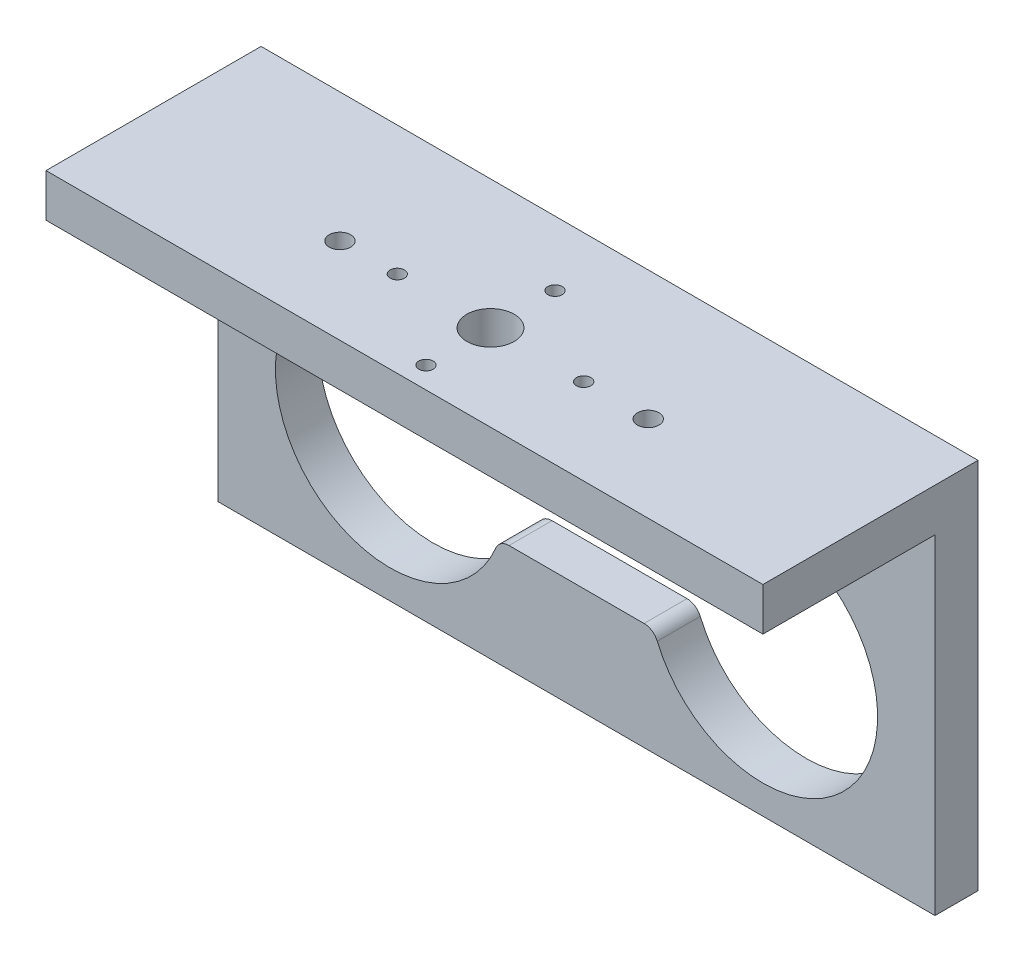
SolidWorks part; units mm, degrees
ref_plane "前视基准面" through (0, 0, 0) normal (0, 0, 1) x (1, 0, 0)
ref_plane "上视基准面" through (0, 0, 0) normal (0, 1, 0) x (1, 0, 0)
ref_plane "右视基准面" through (0, 0, 0) normal (1, 0, 0) x (0, 0, -1)
sketch "草图1" plane through (0, 0, 0) normal (0, 0, 1) x (1, 0, 0)
  line L1 (25, -10) -> (-25, -10)
  line L2 (25, -10) -> (25, 10)
  line L3 (25, 10) -> (-25, 10)
  line L4 (-25, -10) -> (-25, 10)
  line L5 (25, -10) -> (-25, 10) construction
  line L6 (25, 10) -> (-25, -10) construction
  line L8 (-4.7084, 2.5) -> (4.7084, 2.5)
  line L9 (4.7084, -2.5) -> (-4.7084, -2.5)
  line L10 (3.25, 7.25) -> (-3.25, 7.25) construction
  line L11 (3.25, 5.5) -> (-3.25, 5.5)
  line L12 (3.25, 9) -> (-3.25, 9)
  arc A7 (5.6297, -3.1111) -> (5.6297, 3.1111) centre (13, 0) ccw
  arc A8 (-5.6297, 3.1111) -> (-5.6297, -3.1111) centre (-13, 0) ccw
  arc A9 (4.7084, -2.5) -> (5.6297, -3.1111) centre (4.7084, -3.5) cw
  arc A10 (4.7084, 2.5) -> (5.6297, 3.1111) centre (4.7084, 3.5) ccw
  arc A11 (-4.7084, -2.5) -> (-5.6297, -3.1111) centre (-4.7084, -3.5) ccw
  arc A12 (-4.7084, 2.5) -> (-5.6297, 3.1111) centre (-4.7084, 3.5) cw
  arc A13 (3.25, 5.5) -> (3.25, 9) centre (3.25, 7.25) ccw
  arc A14 (-3.25, 9) -> (-3.25, 5.5) centre (-3.25, 7.25) ccw
  point P0 (0, 0)
  point P22 (0, 7.25)
  dimension "D3" = 1
  dimension "D4" = 8
  dimension "D5" = 8
  dimension "D6" = 2.5
  dimension "D8" = 13
  dimension "D9" = 13
  dimension "D12" = 1.75
  dimension "D1" = 20
  dimension "D2" = 50
  dimension "D7" = 2.5
  dimension "D10" = 7.25
  dimension "D11" = 6.5
  dimension "D13" = 3.25
extrude "凸台-拉伸1" add sketch "草图1" along normal blind 3
sketch "草图2" plane through (0, 10, 0) normal (0, 1, 0) x (1, 0, 0)
  line L1 (-25, 0) -> (25, 0)
  line L2 (-25, 0) -> (-25, -15)
  line L3 (-25, -15) -> (25, -15)
  line L4 (25, 0) -> (25, -15)
  dimension "D1" = 15
extrude "凸台-拉伸2" add sketch "草图2" along normal blind 6
sketch "草图5" plane through (0, 10, 0) normal (0, -1, 0) x (1, 0, 0)
  line L1 (25, 3) -> (-25, 3)
  line L2 (25, 3) -> (25, 15)
  line L3 (25, 15) -> (-25, 15)
  line L4 (-25, 3) -> (-25, 15)
extrude "切除-拉伸2" cut sketch "草图5" against normal blind 3
sketch "草图4" plane through (0, 16, 0) normal (0, 1, 0) x (1, 0, 0)
  line L0 (-25, -15) -> (25, -15) construction
  circle A0 centre (0, -9) radius 1.65
  circle A1 centre (6.5, -9) radius 0.5
  circle A2 centre (-6.5, -9) radius 0.5
  circle A3 centre (11, -9) radius 0.75
  circle A4 centre (-10.5, -9) radius 0.75
  circle A5 centre (0, -4.5) radius 0.5
  circle A6 centre (0, -13.5) radius 0.5
  dimension "D1" = 3.3
  dimension "D2" = 1
  dimension "D3" = 6.5
  dimension "D4" = 1
  dimension "D5" = 6.5
  dimension "D6" = 6
  dimension "D7" = 1.5
  dimension "D8" = 1.5
  dimension "D9" = 10.5
  dimension "D10" = 11
  dimension "D11" = 1
  dimension "D12" = 1
  dimension "D13" = 4.5
  dimension "D14" = 4.5
extrude "切除-拉伸1" cut sketch "草图4" against normal up to surface (3 mm away) up to face at (0, 13, 9)
